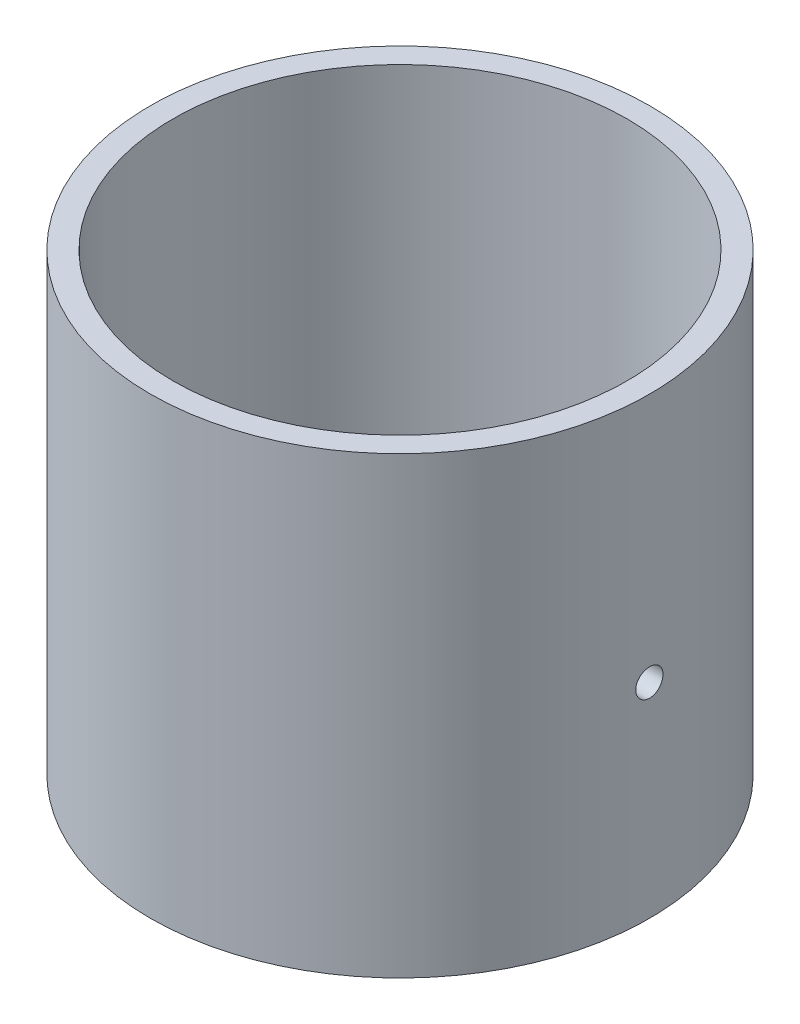
SolidWorks part; units mm, degrees
ref_plane "Ön Düzlem" through (0, 0, 0) normal (0, 0, 1) x (1, 0, 0)
ref_plane "Üst Düzlem" through (0, 0, 0) normal (0, 1, 0) x (1, 0, 0)
ref_plane "Sağ Düzlem" through (0, 0, 0) normal (1, 0, 0) x (0, 0, -1)
sketch "Sketch2" plane through (0, 0, 0) normal (0, 0, 1) x (1, 0, 0)
  line L0 (-37.7243, 79.0743) -> (-37.7243, -20.9257)
  line L1 (-37.7243, -20.9257) -> (17.2757, -20.9257)
  line L2 (17.2757, -20.9257) -> (17.2757, 79.0743)
  line L3 (17.2757, 79.0743) -> (-37.7243, 79.0743)
revolve "Revolve1" add sketch "Sketch2" angle 360 about L2
sketch "Sketch3" plane through (0, 79.0743, 0) normal (0, 1, 0) x (1, 0, 0)
  circle A0 centre (17.2757, 0) radius 50
  circle A1 centre (17.2757, 0) radius 55 construction
  dimension "D1" = 100
  dimension "D2" = 5
extrude "Cut-Extrude2" cut sketch "Sketch3" against normal blind 95
ref_plane "Plane1" through (75, 0, 0) normal (1, 0, 0) x (0, 0, -1)
sketch "Sketch5" plane through (75, 0, 0) normal (1, 0, 0) x (0, 0, -1)
  circle A0 centre (0, 24.0743) radius 3
  dimension "D1" = 6
extrude "Cut-Extrude4" cut sketch "Sketch5" against normal blind 49
